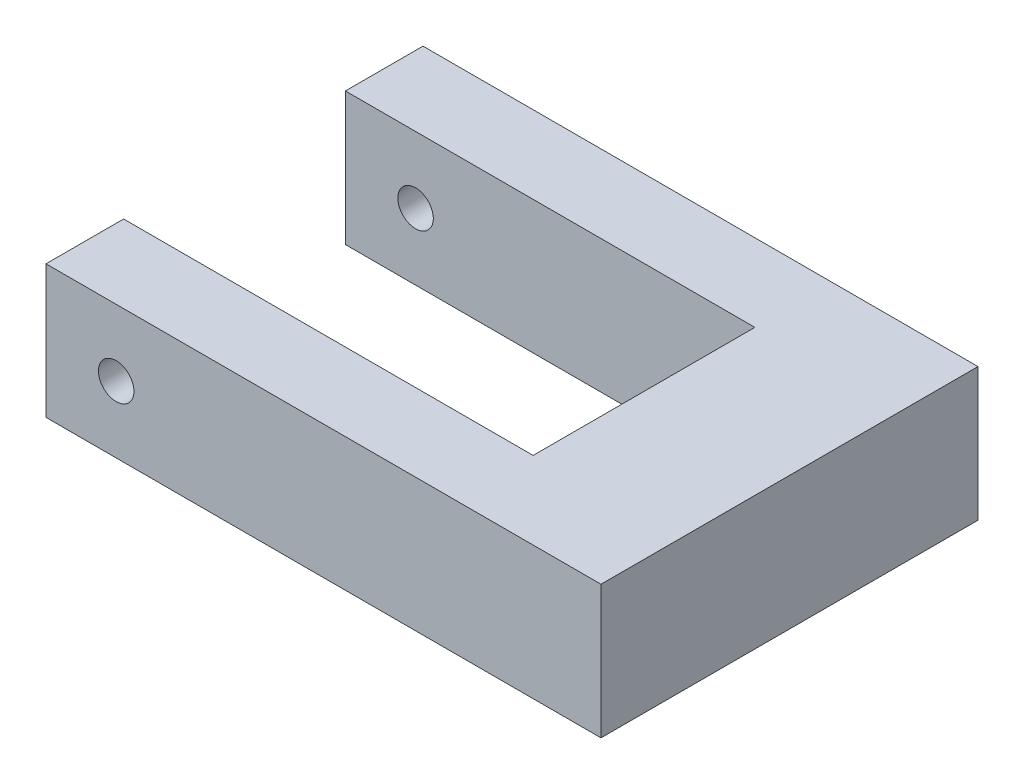
SolidWorks part; units mm, degrees
ref_plane "Спереди" through (0, 0, 0) normal (0, 0, 1) x (1, 0, 0)
ref_plane "Сверху" through (0, 0, 0) normal (0, 1, 0) x (1, 0, 0)
ref_plane "Справа" through (0, 0, 0) normal (1, 0, 0) x (0, 0, -1)
sketch "Эскиз1" plane through (0, 0, 0) normal (0, 0, 1) x (1, 0, 0)
  line L0 (0, 5.9581) -> (0, -24.0419)
  line L3 (0, -24.0419) -> (125.1317, -24.0419)
  line L4 (0, 5.9581) -> (125.1317, 5.9581)
  line L5 (125.1317, 5.9581) -> (125.1317, -24.0419)
  line L6 (15.824, -9.0419) -> (68.2142, -9.0419) construction
  dimension "D2" = 15
extrude "Вытянуть1" add sketch "Эскиз1" against normal blind 85 from offset 7.5
sketch "Эскиз3" plane through (0, 0, 0) normal (0, 1, 0) x (1, 0, 0)
  line L0 (-2.2661, 60) -> (92.3282, 60)
  line L1 (92.3282, 60) -> (92.3282, 10)
  line L2 (92.3282, 10) -> (-2.2661, 10)
  line L4 (-2.2661, 10) -> (-2.2661, 60)
  line L8 (125.1317, 77.5) -> (0, 77.5) construction
  line L9 (125.1317, -7.5) -> (0, -7.5) construction
  dimension "D2" = 17.5
  dimension "D3" = 17.5
extrude "Вырез-Вытянуть1" cut sketch "Эскиз3" against normal mid plane 87
sketch "Эскиз4" plane through (0, 0, 0) normal (0, 0, 1) x (1, 0, 0)
  circle A0 centre (15.824, -9.0419) radius 4
  dimension "D1" = 8
extrude "Вырез-Вытянуть2" cut sketch "Эскиз4" against normal mid plane 200
